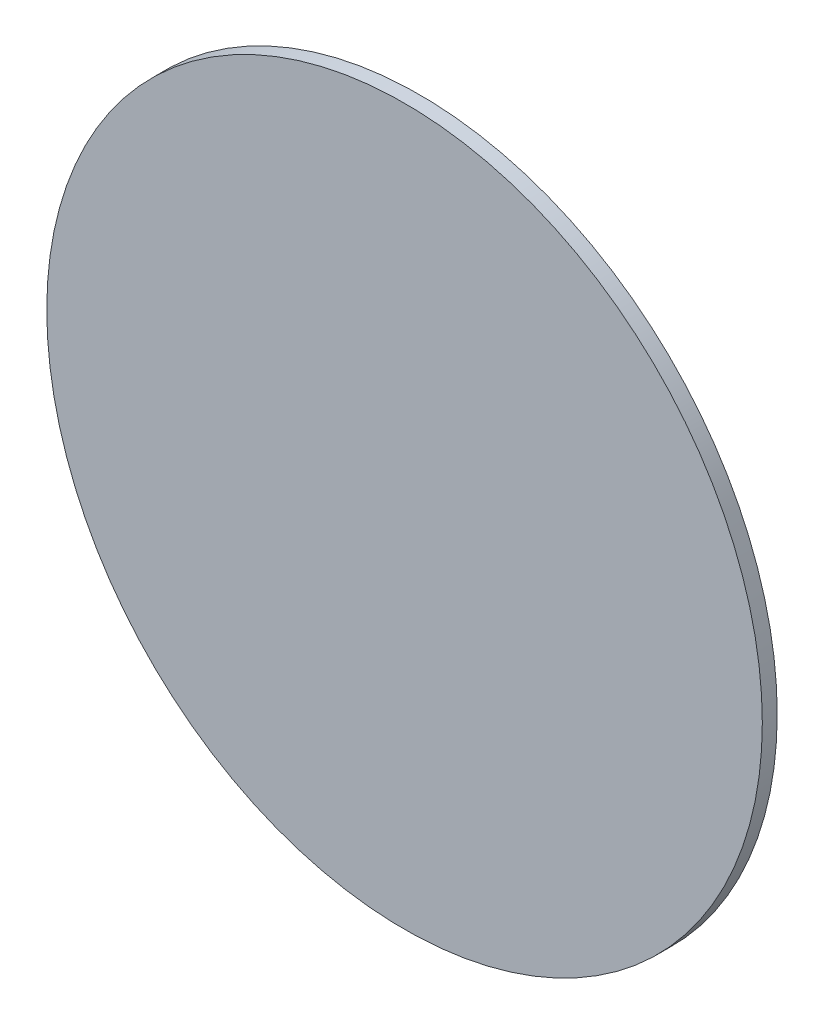
SolidWorks part; units mm, degrees
material "Сплав 2024"
ref_plane "Спереди" through (0, 0, 0) normal (0, 0, 1) x (1, 0, 0)
ref_plane "Сверху" through (0, 0, 0) normal (0, 1, 0) x (1, 0, 0)
ref_plane "Справа" through (0, 0, 0) normal (1, 0, 0) x (0, 0, -1)
sketch "Эскиз1" plane through (0, 0, 0) normal (0, 0, 1) x (1, 0, 0)
  circle A0 centre (0, 0) radius 24
  dimension "D1" = 48
extrude "Бобышка-Вытянуть1" add sketch "Эскиз1" along normal blind 1
